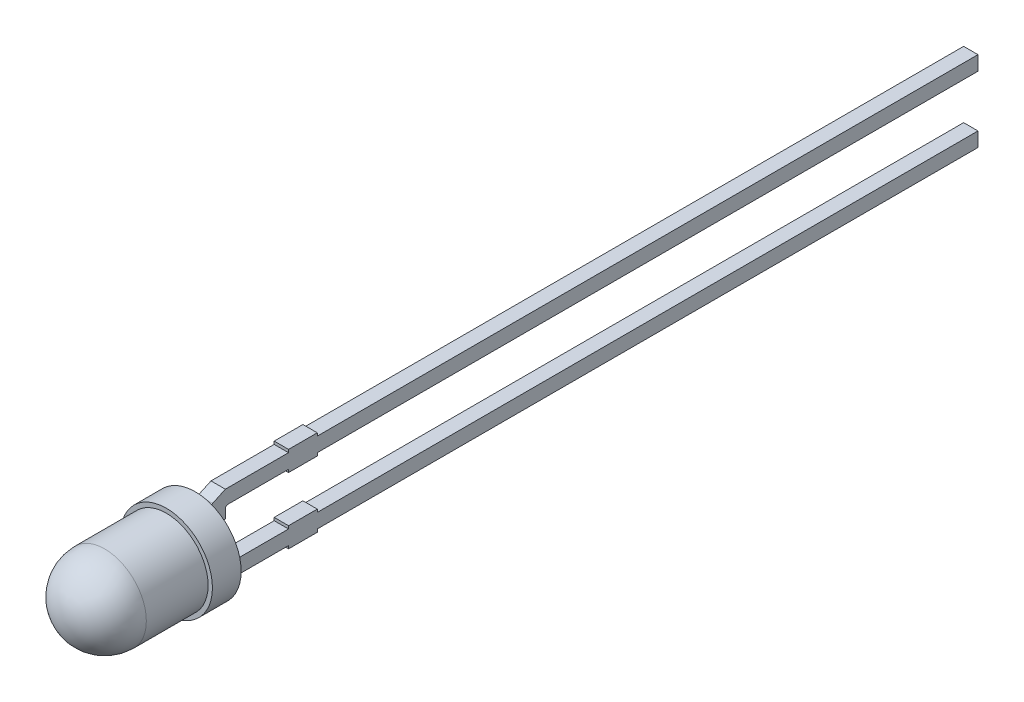
SolidWorks part; units mm, degrees
ref_plane "Front" through (0, 0, 0) normal (0, 0, 1) x (1, 0, 0)
ref_plane "Top" through (0, 0, 0) normal (0, 1, 0) x (1, 0, 0)
ref_plane "Right" through (0, 0, 0) normal (1, 0, 0) x (0, 0, -1)
sketch "Sketch1" plane through (0, 0, 0) normal (1, 0, 0) x (0, 0, -1)
  line L0 (0, 0) -> (76.2974, 0) construction
  line L1 (0, 1.45) -> (2.15, 1.45)
  line L2 (2.15, 1.45) -> (2.15, 1.6)
  line L3 (2.15, 1.6) -> (3.15, 1.6)
  line L4 (3.15, 1.6) -> (3.15, 0)
  line L5 (3.15, 0) -> (-1.45, 0)
  arc A0 (0, 1.45) -> (-1.45, 0) centre (0, 0) ccw
  dimension "D1" = 1.45
  dimension "D2" = 4.6
  dimension "D3" = 1
  dimension "D4" = 1.6
revolve "Revolve1" add sketch "Sketch1" angle 360 about L0
sketch "Sketch2" plane through (0, 0, 0) normal (1, 0, 0) x (0, 0, -1)
  line L0 (3.15, -1.6) -> (3.15, 1.6) construction
  line L1 (3.15, -1.6) -> (3.15, 1.6) construction
  line L2 (3.15, 1.027) -> (3.95, 1.4)
  line L3 (3.95, 1.4) -> (6.15, 1.4)
  line L4 (6.15, 1.4) -> (6.15, 1.5)
  line L5 (6.15, 1.5) -> (7.15, 1.5)
  line L6 (7.15, 1.5) -> (7.15, 1.4)
  line L7 (7.15, 1.4) -> (30.15, 1.4)
  line L8 (30.15, 1.4) -> (30.15, 0.9)
  line L9 (30.15, 0.9) -> (7.15, 0.9)
  line L10 (7.15, 0.9) -> (7.15, 0.8)
  line L11 (7.15, 0.8) -> (6.15, 0.8)
  line L12 (6.15, 0.8) -> (6.15, 0.9)
  line L13 (6.15, 0.9) -> (4.05, 0.9)
  line L14 (3.95, 0.8) -> (3.95, 0.5)
  line L15 (3.95, 0.5) -> (3.15, 0.5)
  line L16 (3.15, 0) -> (7.9733, 0) construction
  line L17 (3.15, 1.027) -> (3.15, 0.5)
  line L18 (3.95, -0.8) -> (3.95, -0.5)
  line L19 (6.15, -0.9) -> (4.05, -0.9)
  line L20 (6.15, -0.8) -> (6.15, -0.9)
  line L21 (7.15, -0.8) -> (6.15, -0.8)
  line L22 (7.15, -0.9) -> (7.15, -0.8)
  line L23 (30.15, -0.9) -> (7.15, -0.9)
  line L24 (30.15, -1.4) -> (30.15, -0.9)
  line L25 (7.15, -1.4) -> (30.15, -1.4)
  line L26 (7.15, -1.5) -> (7.15, -1.4)
  line L27 (6.15, -1.5) -> (7.15, -1.5)
  line L28 (6.15, -1.4) -> (6.15, -1.5)
  line L29 (3.95, -1.4) -> (6.15, -1.4)
  line L30 (3.15, -1.027) -> (3.95, -1.4)
  line L31 (3.15, -1.027) -> (3.15, -0.5)
  line L32 (3.95, -0.5) -> (3.15, -0.5)
  arc A0 (4.05, 0.9) -> (3.95, 0.8) centre (4.05, 0.8) ccw
  arc A1 (4.05, -0.9) -> (3.95, -0.8) centre (4.05, -0.8) cw
  point P19 (3.15, 0)
  dimension "D1" = 0.5
  dimension "D2" = 0.7
  dimension "D3" = 1.4
  dimension "D4" = 0.8
  dimension "D5" = 27
  dimension "D6" = 115
  dimension "D7" = 4
  dimension "D8" = 1
  dimension "D9" = 0.5
  dimension "D10" = 0.1
extrude "Extrude1" add sketch "Sketch2" along normal mid plane 0.5
fillet "Fillet1" radius 0.25 8 edges at (0, -0.5, -3.15) (0, -1.027, -3.15) (-0.25, -0.7635, -3.15) (0, 0.5, -3.15) (-0.25, 0.7635, -3.15) (0, 1.027, -3.15) (0.25, 0.7635, -3.15) (0.25, -0.7635, -3.15)
